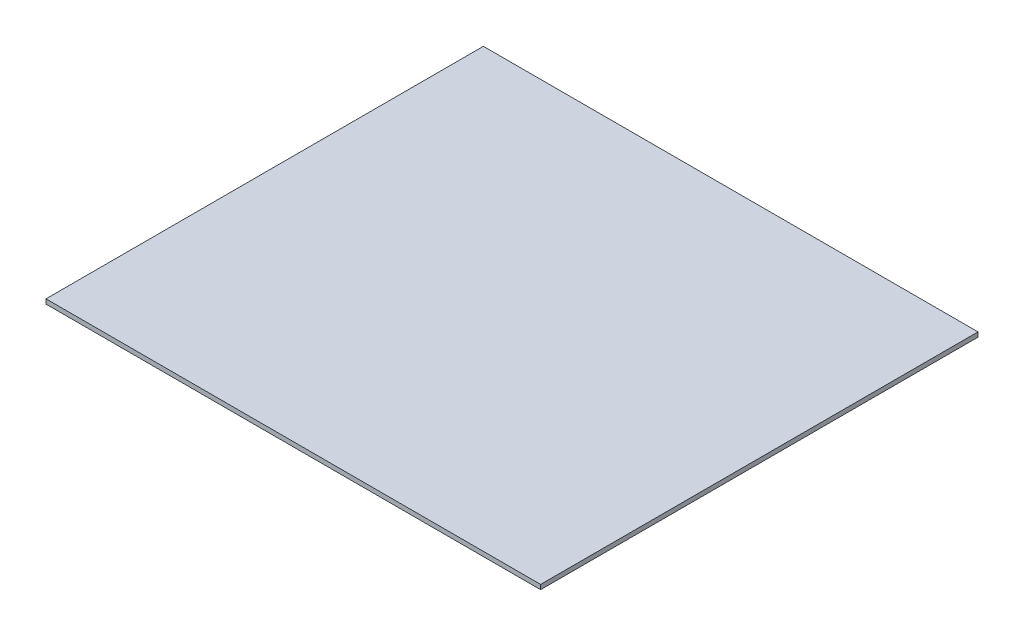
SolidWorks part; units mm, degrees
material "Pine"
ref_plane "Front Plane" through (0, 0, 0) normal (0, 0, 1) x (1, 0, 0)
ref_plane "Top Plane" through (0, 0, 0) normal (0, 1, 0) x (1, 0, 0)
ref_plane "Right Plane" through (0, 0, 0) normal (1, 0, 0) x (0, 0, -1)
sketch "Sketch1" plane through (0, 0, 0) normal (0, 1, 0) x (1, 0, 0)
  line L1 (-287.2212, -371.4876) -> (398.5788, -371.4876)
  line L2 (-287.2212, -371.4876) -> (-287.2212, 234.9374)
  line L3 (-287.2212, 234.9374) -> (398.5788, 234.9374)
  line L4 (398.5788, -371.4876) -> (398.5788, 234.9374)
  dimension "D1" = 685.8
  dimension "D2" = 606.425
extrude "Boss-Extrude1" add sketch "Sketch1" along normal blind 6.35 contours L2 L3 L4 L1
